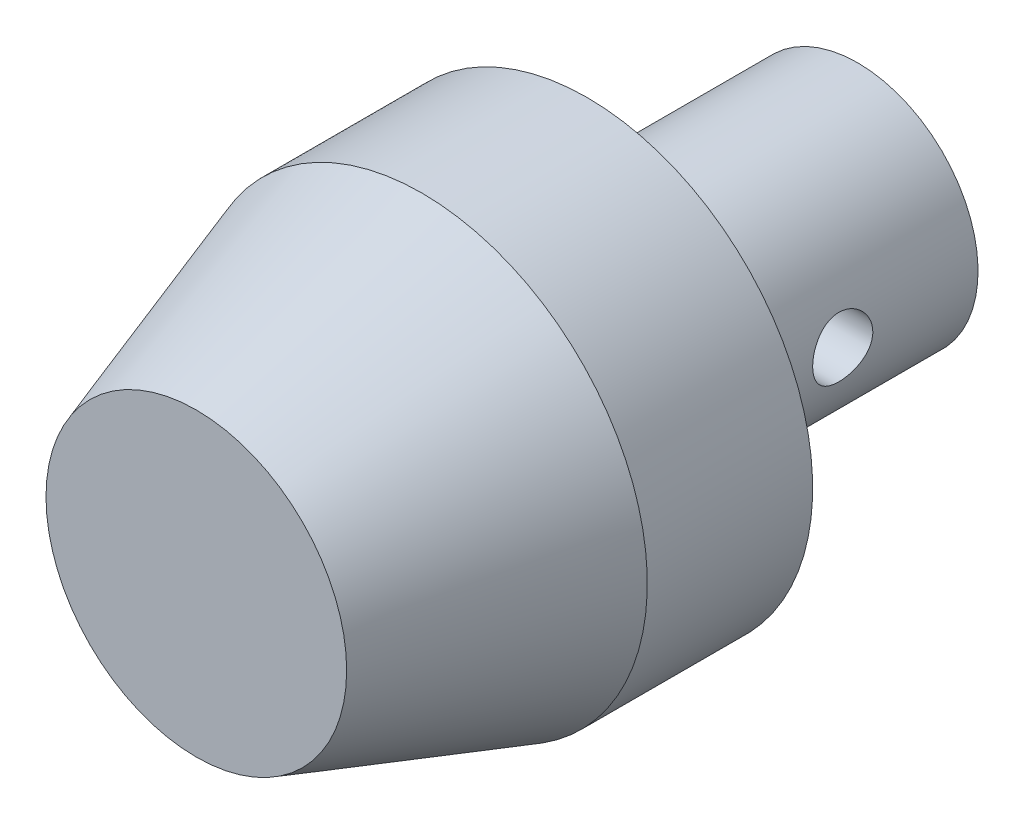
SolidWorks part; units mm, degrees
ref_plane "前基準面" through (0, 0, 0) normal (0, 0, 1) x (1, 0, 0)
ref_plane "上基準面" through (0, 0, 0) normal (0, 1, 0) x (1, 0, 0)
ref_plane "右基準面" through (0, 0, 0) normal (1, 0, 0) x (0, 0, -1)
sketch "草圖1" plane through (0, 0, 0) normal (1, 0, 0) x (0, 0, -1)
  line L0 (0, 0) -> (0, 10)
  line L1 (0, 10) -> (15, 15)
  line L2 (15, 15) -> (26, 15)
  line L3 (26, 15) -> (26, 8)
  line L4 (26, 8) -> (44, 8)
  line L5 (44, 8) -> (44, 0)
  line L6 (44, 0) -> (0, 0)
  dimension "D1" = 15
  dimension "D2" = 10
  dimension "D3" = 15
  dimension "D4" = 11
  dimension "D5" = 18
  dimension "D6" = 8
revolve "旋轉1" add sketch "草圖1" angle 360 about L6
sketch "草圖2" plane through (0, 0, 0) normal (1, 0, 0) x (0, 0, -1)
  line L0 (44, -8) -> (44, 8) construction
  circle A0 centre (35, 0) radius 2
  dimension "D1" = 9
  dimension "D2" = 4
extrude "除料-伸長1" cut sketch "草圖2" against normal mid plane 20
